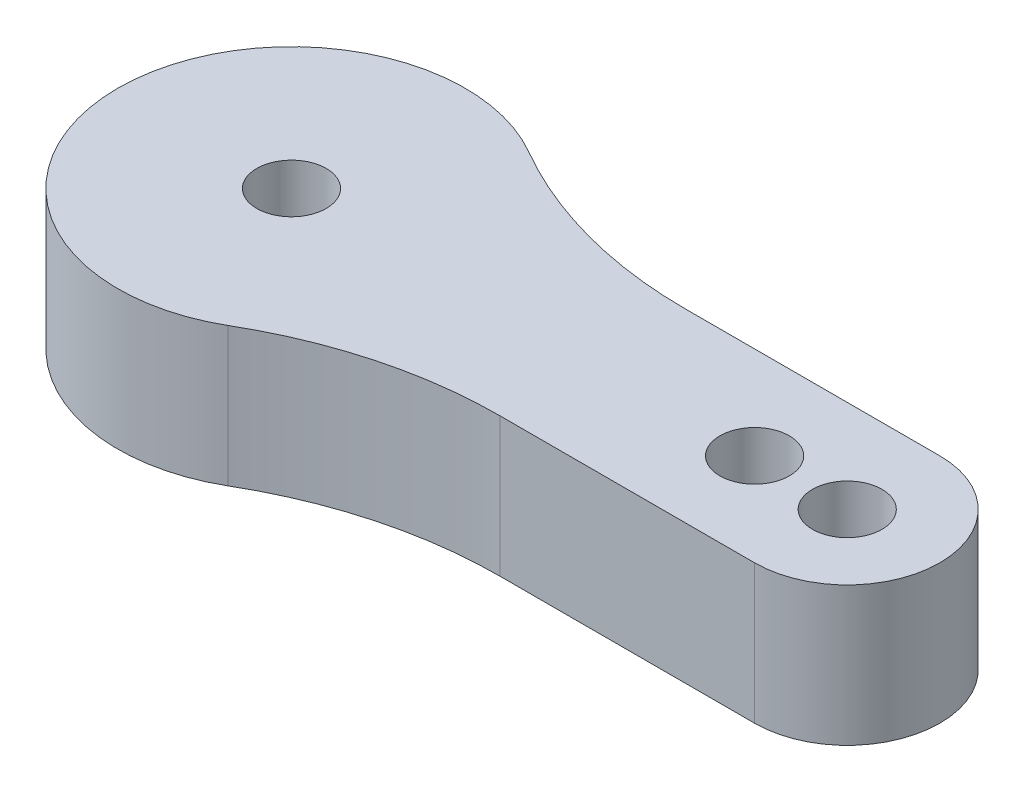
SolidWorks part; units mm, degrees
material "1060 合金"
ref_plane "前视基准面" through (0, 0, 0) normal (0, 0, 1) x (1, 0, 0)
ref_plane "上视基准面" through (0, 0, 0) normal (0, 1, 0) x (1, 0, 0)
ref_plane "右视基准面" through (0, 0, 0) normal (1, 0, 0) x (0, 0, -1)
sketch "草图3" plane through (0, 0, 0) normal (0, 1, 0) x (1, 0, 0)
  line L0 (16.3683, 14) -> (5.3683, 14)
  line L5 (25.7195, 10) -> (-7.6317, 10) construction
  line L6 (-7.6317, 10) -> (-3.8817, 16.4952) construction
  line L7 (-7.6317, 10) -> (-15.1317, 10) construction
  line L8 (16.3683, 6) -> (5.3683, 6)
  circle A0 centre (-7.6317, 10) radius 1.5
  circle A1 centre (12.3683, 10) radius 1.5
  circle A2 centre (16.3683, 10) radius 1.5
  arc A4 (-3.8817, 16.4952) -> (-3.8817, 3.5048) centre (-7.6317, 10) ccw
  arc A6 (16.3683, 6) -> (16.3683, 14) centre (16.3683, 10) ccw
  arc A7 (5.3683, 14) -> (-3.8817, 16.4952) centre (5.3683, 32.3931) cw
  arc A11 (5.3683, 6) -> (-3.8817, 3.5048) centre (5.3683, -12.3931) ccw
  point P4 (3.6231, 10)
  dimension "D1" = 3
  dimension "D2" = 3
  dimension "D4" = 3
  dimension "D6" = 15
  dimension "D7" = 60
  dimension "D9" = 4
  dimension "D3" = 11
  dimension "D5" = 4
  dimension "D8" = 24
extrude "凸台-拉伸1" add sketch "草图3" along normal blind 6 from offset 0
